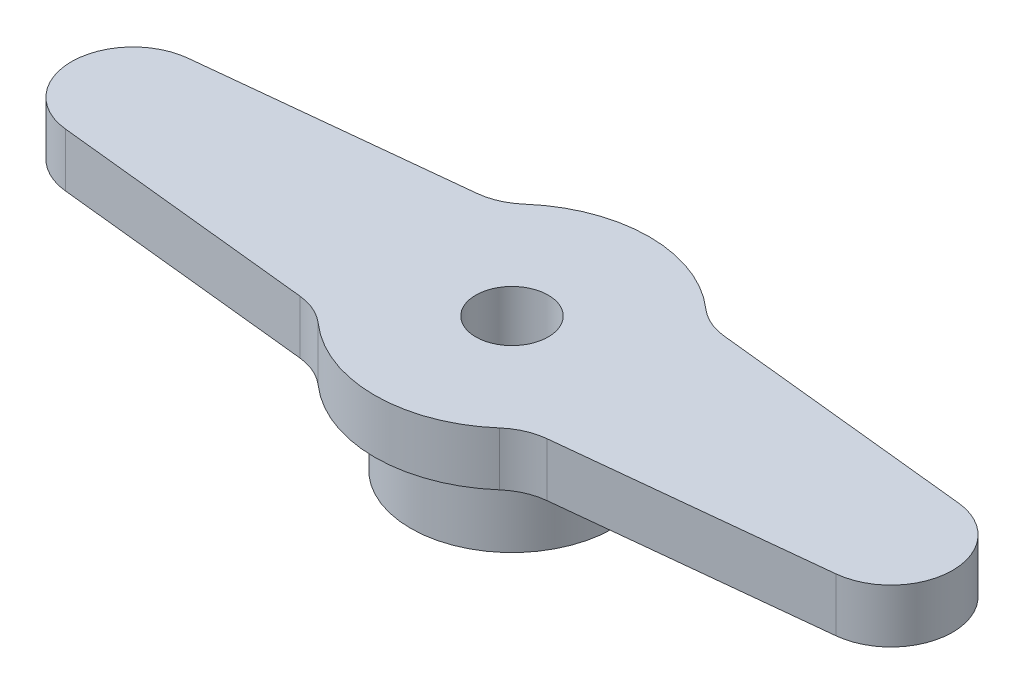
SolidWorks part; units mm, degrees
ref_plane "Front Plane" through (0, 0, 0) normal (0, 0, 1) x (1, 0, 0)
ref_plane "Top Plane" through (0, 0, 0) normal (0, 1, 0) x (1, 0, 0)
ref_plane "Right Plane" through (0, 0, 0) normal (1, 0, 0) x (0, 0, -1)
sketch "Sketch1" plane through (0, 0, 0) normal (0, 1, 0) x (1, 0, 0)
  circle A0 centre (0, 0) radius 4.3688
  circle A1 centre (0, 0) radius 3.048
  dimension "D1" = 8.7376
  dimension "D2" = 6.096
extrude "Boss-Extrude1" add sketch "Sketch1" along normal blind 3.429
sketch "Sketch2" plane through (0, 3.429, 0) normal (0, 1, 0) x (1, 0, 0)
  line L0 (0, 0) -> (18.9865, 0) construction
  line L1 (0, 0) -> (0, 8.1885) construction
  line L2 (5.3227, 3.8238) -> (16.6072, 2.6416)
  line L3 (5.3227, -3.8238) -> (16.6072, -2.6416)
  line L4 (-5.3227, -3.8238) -> (-16.6072, -2.6416)
  line L5 (-5.3227, 3.8238) -> (-16.6072, 2.6416)
  arc A0 (3.9095, 4.4431) -> (-3.9095, 4.4431) centre (0, 0) ccw
  arc A1 (16.6072, 2.6416) -> (16.6072, -2.6416) centre (16.3304, 0) cw
  arc A2 (5.3227, 3.8238) -> (3.9095, 4.4431) centre (5.5874, 6.35) cw
  arc A3 (5.3227, -3.8238) -> (3.9095, -4.4431) centre (5.5874, -6.35) ccw
  arc A4 (-5.3227, -3.8238) -> (-3.9095, -4.4431) centre (-5.5874, -6.35) cw
  arc A5 (-5.3227, 3.8238) -> (-3.9095, 4.4431) centre (-5.5874, 6.35) ccw
  arc A6 (-16.6072, 2.6416) -> (-16.6072, -2.6416) centre (-16.3304, 0) ccw
  arc A7 (-3.9095, -4.4431) -> (3.9095, -4.4431) centre (0, 0) ccw
  dimension "D1" = 11.8364
  dimension "D5" = 2.54
  dimension "D2" = 7.6477
  dimension "D3" = 6.35
  dimension "D4" = 5.2832
extrude "Boss-Extrude2" add sketch "Sketch2" along normal blind 2.3114
sketch "Sketch3" plane through (0, 5.7404, 0) normal (0, 1, 0) x (1, 0, 0)
  circle A0 centre (0, 0) radius 1.5621
  dimension "D1" = 3.1242
extrude "Cut-Extrude1" cut sketch "Sketch3" against normal through all
